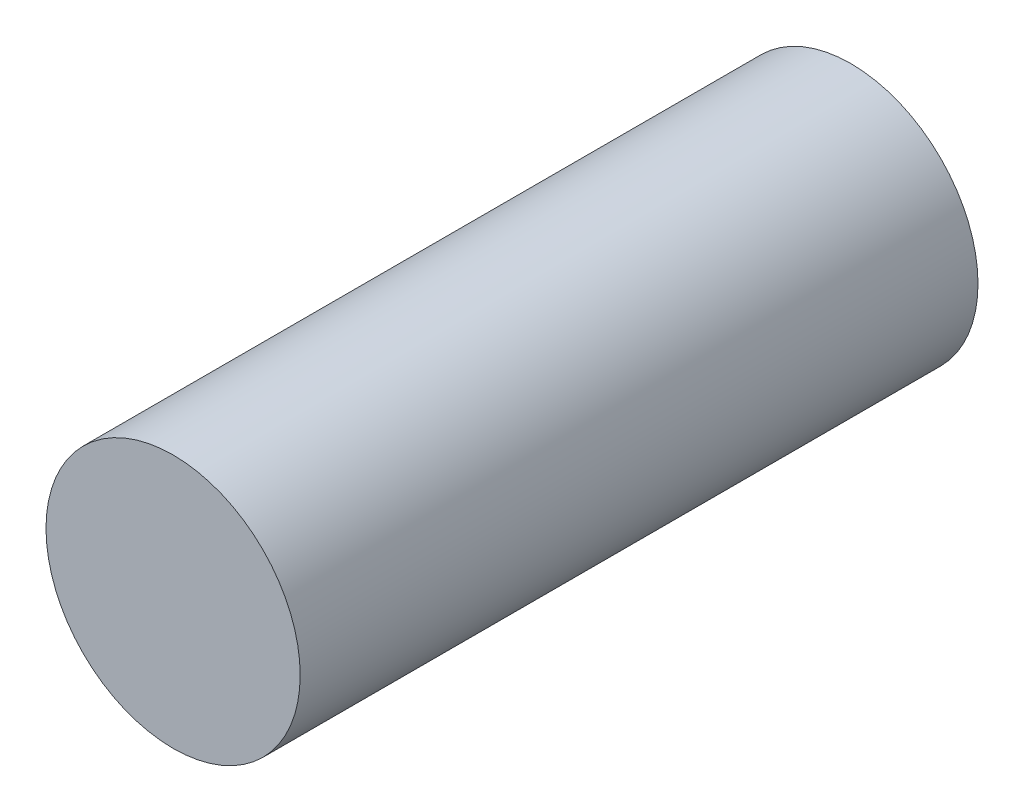
SolidWorks part; units mm, degrees
ref_plane "前视基准面" through (0, 0, 0) normal (0, 0, 1) x (1, 0, 0)
ref_plane "上视基准面" through (0, 0, 0) normal (0, 1, 0) x (1, 0, 0)
ref_plane "右视基准面" through (0, 0, 0) normal (1, 0, 0) x (0, 0, -1)
other "Configuration Table"
sketch "草图1" plane through (0, 0, 0) normal (0, 0, 1) x (1, 0, 0)
  circle A0 centre (0, 0) radius 3
extrude "Shaft_D6_L16" add sketch "草图1" along normal blind 16
